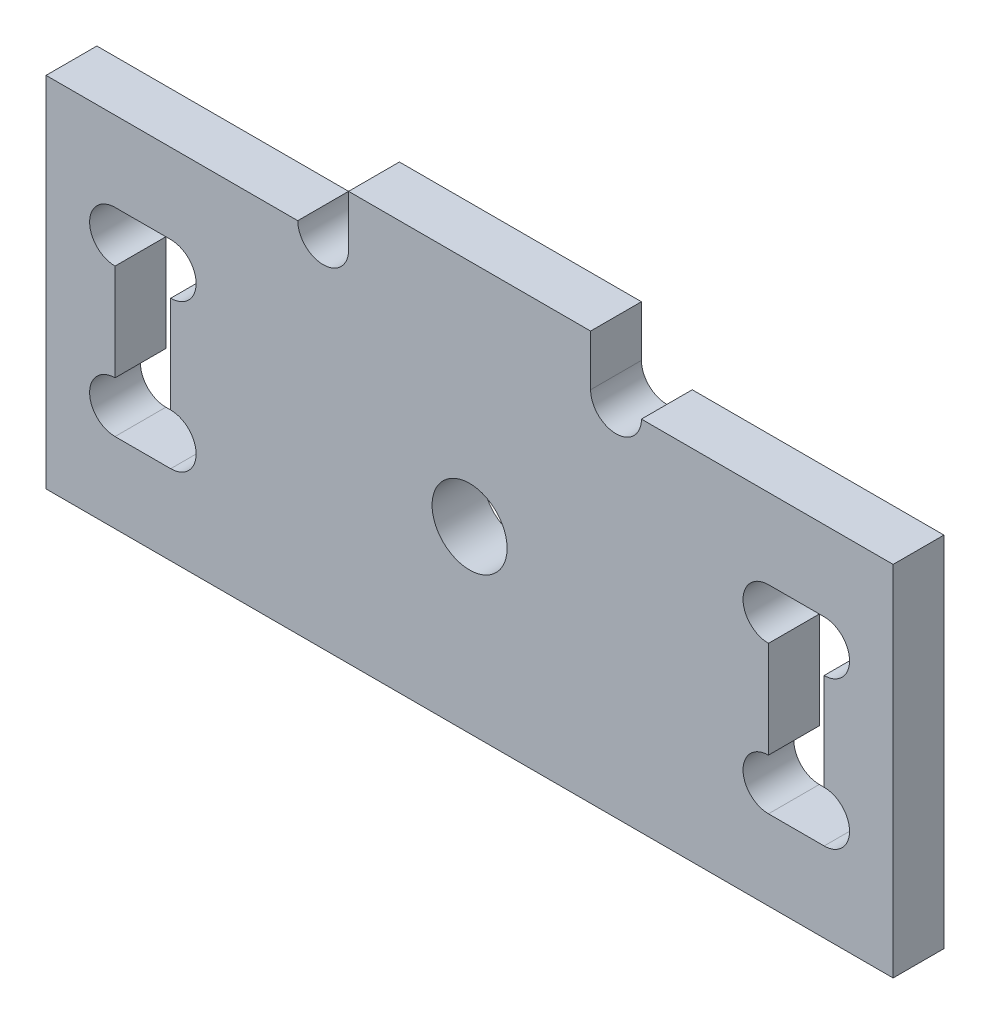
SolidWorks part; units mm, degrees
material "Thornel Mat VMA"
ref_plane "前视基准面" through (0, 0, 0) normal (0, 0, 1) x (1, 0, 0)
ref_plane "上视基准面" through (0, 0, 0) normal (0, 1, 0) x (1, 0, 0)
ref_plane "右视基准面" through (0, 0, 0) normal (1, 0, 0) x (0, 0, -1)
sketch "草图1" plane through (0, 0, 0) normal (0, 0, 1) x (1, 0, 0)
  line L0 (0, 0.1) -> (0, 9.5) construction
  line L1 (17.5, -7.4) -> (-17.5, -7.4)
  line L2 (17.5, -7.4) -> (17.5, 7.4)
  line L3 (17.5, 7.4) -> (5, 7.4)
  line L4 (-17.5, -7.4) -> (-17.5, 7.4)
  line L5 (17.5, -7.4) -> (-17.5, 7.4) construction
  line L6 (17.5, 7.4) -> (-17.5, -7.4) construction
  line L7 (-12.35, -4.1) -> (-14.65, -4.1)
  line L8 (-12.35, -4.1) -> (-12.35, 4.1)
  line L9 (-12.35, 4.1) -> (-14.65, 4.1)
  line L10 (-14.65, -4.1) -> (-14.65, 4.1)
  line L11 (-12.35, -4.1) -> (-14.65, 4.1) construction
  line L12 (-12.35, 4.1) -> (-14.65, -4.1) construction
  line L13 (12.35, 4.1) -> (14.65, 4.1)
  line L14 (14.65, -4.1) -> (14.65, 4.1)
  line L15 (12.35, -4.1) -> (14.65, -4.1)
  line L16 (12.35, -4.1) -> (12.35, 4.1)
  line L17 (13.5, 4.1) -> (13.5, 0.0975) construction
  line L18 (-5, 7.4) -> (-5, 9.5)
  line L19 (-5, 9.5) -> (5, 9.5)
  line L20 (5, 9.5) -> (5, 7.4)
  line L21 (-5, 7.4) -> (-17.5, 7.4)
  circle A0 centre (0, 0.1) radius 1.55 construction
  circle A1 centre (-14.65, 3.05) radius 1.05
  circle A2 centre (-12.35, 3.05) radius 1.05
  circle A3 centre (-14.65, -3.05) radius 1.05
  circle A4 centre (-12.35, -3.05) radius 1.05
  circle A5 centre (14.65, -3.05) radius 1.05
  circle A6 centre (14.65, 3.05) radius 1.05
  circle A7 centre (12.35, -3.05) radius 1.05
  circle A8 centre (12.35, 3.05) radius 1.05
  circle A9 centre (6.05, 7.4) radius 1.05
  circle A10 centre (-6.05, 7.4) radius 1.05
  circle A11 centre (0, 0) radius 1.55
  point P0 (0, 0)
  point P8 (-13.5, 0)
  dimension "D1" = 3.1
  dimension "D5" = 2.1
  dimension "D2" = 7.3
  dimension "D3" = 35
  dimension "D4" = 7.5
  dimension "D6" = 8.2
  dimension "D7" = 7.4
  dimension "D8" = 2.3
  dimension "D9" = 27
  dimension "D10" = 10
  dimension "D11" = 2.1
  dimension "D12" = 0
extrude "凸台-拉伸1" add sketch "草图1" along normal blind 2.1 contours A10 L21 L4 L1 L2 L3 A9 L20 L19 L18 A4 L7 A3 L10 A1 L9 A2 L8 A0 L16 A8 L13 A6 L14 A5 L15 A7
